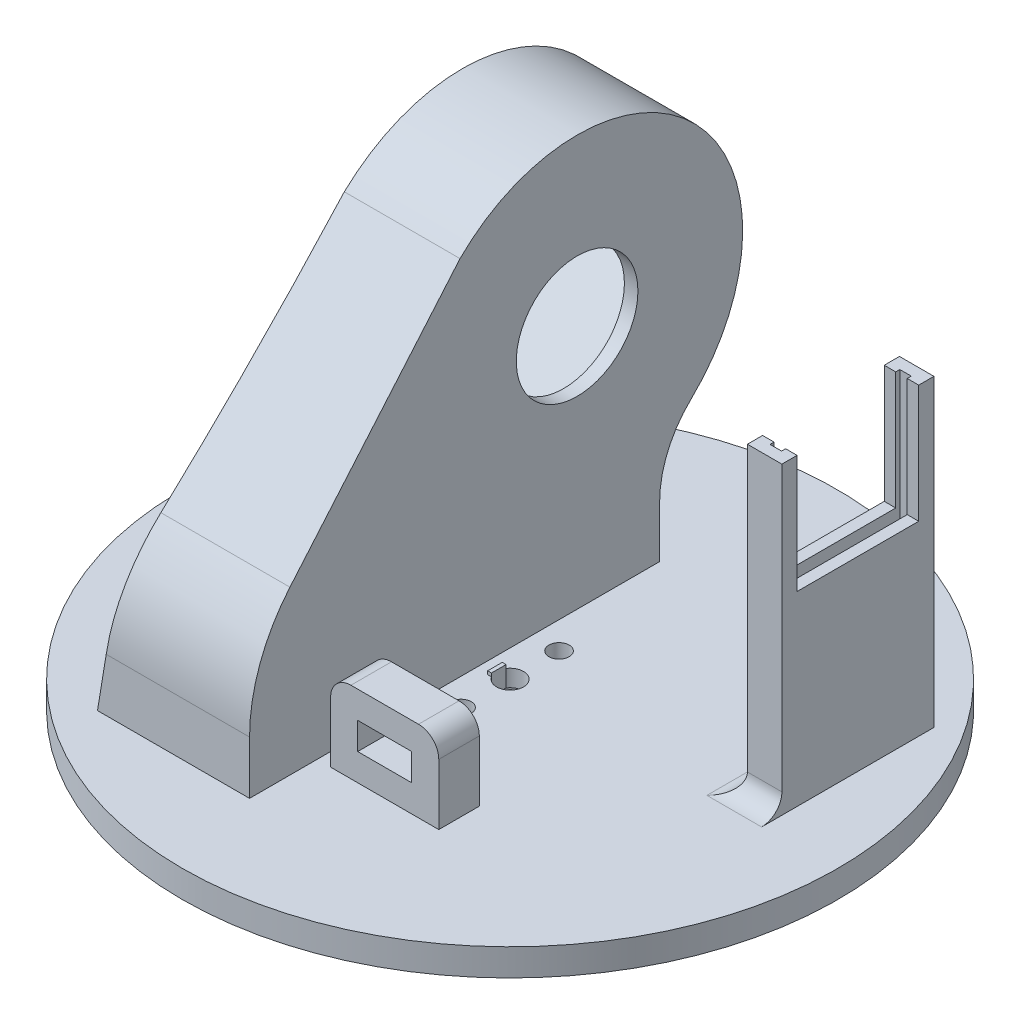
SolidWorks part; units mm, degrees
ref_plane "Front Plane" through (0, 0, 0) normal (0, 0, 1) x (1, 0, 0)
ref_plane "Top Plane" through (0, 0, 0) normal (0, 1, 0) x (1, 0, 0)
ref_plane "Right Plane" through (0, 0, 0) normal (1, 0, 0) x (0, 0, -1)
sketch "Sketch2" plane through (0, 0, 0) normal (0, 1, 0) x (1, 0, 0)
  circle A0 centre (0, 0) radius 48.5
  dimension "D1" = 97
extrude "Boss-Extrude1" add sketch "Sketch2" along normal blind 4
sketch "Sketch4" plane through (0, 0, 0) normal (0, -1, 0) x (1, 0, 0)
  circle A0 centre (0, 7.25) radius 1.5
  circle A1 centre (0, -7.25) radius 1.5
  dimension "D1" = 3
  dimension "D2" = 3
  dimension "D3" = 14.5
  dimension "D4" = 7.25
extrude "Cut-Extrude2" cut sketch "Sketch4" against normal through all
sketch "Sketch5" plane through (0, 0, 0) normal (0, -1, 0) x (1, 0, 0)
  circle A0 centre (0, 0) radius 3.75
  dimension "D1" = 7.5
extrude "Cut-Extrude3" cut sketch "Sketch5" against normal blind 1.5
ref_plane "Plane1" through (-4, 0, 0) normal (1, 0, 0) x (0, 0, -1)
sketch "Sketch7" plane through (-4, 0, 0) normal (1, 0, 0) x (0, 0, -1)
  line L0 (23.1299, 11.6445) -> (23.1299, 4)
  line L5 (48.5, 4) -> (-48.5, 4) construction
  line L6 (-27.2273, 29.5362) -> (-1.2843, 55.4793)
  line L7 (-43.5609, 4) -> (23.1299, 4)
  line L11 (-34.5496, 4) -> (-34.5496, 11.8586)
  arc A4 (28.7298, 24.692) -> (-1.2843, 55.4793) centre (13.9185, 40.2765) ccw
  arc A5 (28.7298, 24.692) -> (23.1299, 11.6445) centre (41.1299, 11.6445) ccw
  arc A6 (-27.2273, 29.5362) -> (-34.5496, 11.8586) centre (-9.5496, 11.8586) ccw
  dimension "D1" = 25
  dimension "D4" = 43
  dimension "D3" = 18
  dimension "D5" = 45
extrude "Boss-Extrude2" add sketch "Sketch7" against normal blind 14
ref_plane "Plane2" through (-6, 0, 0) normal (1, 0, 0) x (0, 0, -1)
sketch "Sketch8" plane through (-6, 0, 0) normal (1, 0, 0) x (0, 0, -1)
  line L0 (-27.2273, 29.5362) -> (-1.2843, 55.4793) construction
  line L1 (-15.2496, 25.9576) -> (13.7417, 54.9489)
  line L2 (-15.2496, 25.9576) -> (-0.4004, 11.1083)
  line L3 (-0.4004, 11.1083) -> (28.591, 40.0997)
  line L4 (13.7417, 54.9489) -> (28.591, 40.0997)
  line L5 (-15.2496, 25.9576) -> (28.591, 40.0997) construction
  line L6 (-0.4004, 11.1083) -> (13.7417, 54.9489) construction
  point P0 (6.6707, 33.0286)
  point P11 (13.9185, 40.2765)
  dimension "D1" = 41
  dimension "D2" = 21
  dimension "D3" = 90
  dimension "D4" = 20.5
  dimension "D5" = 90
  dimension "D6" = 10.25
  dimension "D7" = 10.5
extrude "Cut-Extrude5" cut sketch "Sketch8" against normal up to next
sketch "Sketch9" plane through (-18, 0, 0) normal (-1, 0, 0) x (0, 0, 1)
  line L0 (-13.7417, 54.9489) -> (-28.591, 40.0997) construction
  line L3 (-21.1664, 47.5243) -> (-22.536, 48.894) construction
  circle A0 centre (-20.1057, 53.5347) radius 1.3
  circle A1 centre (-27.1768, 46.4637) radius 1.3
  circle A2 centre (6.7644, 12.5225) radius 1.3
  circle A3 centre (13.8354, 19.5936) radius 1.3
  dimension "D1" = 2.6
  dimension "D5" = 5
  dimension "D6" = 90
  dimension "D2" = 3.5
  dimension "D3" = 2
  dimension "D4" = 2
extrude "Cut-Extrude6" cut sketch "Sketch9" against normal blind 7.5
sketch "Sketch11" plane through (-4, 0, 0) normal (1, 0, 0) x (0, 0, -1)
  circle A0 centre (13.9185, 40.2765) radius 9
  dimension "D1" = 18
extrude "Cut-Extrude9" cut sketch "Sketch11" against normal up to next
sketch "Sketch17" plane through (-18, 0, 0) normal (-1, 0, 0) x (0, 0, 1)
  line L0 (29.3486, 31.6576) -> (3.4056, 57.6006)
  line L1 (-26.1299, 11.6445) -> (-26.1299, 1)
  line L2 (-26.1299, 1) -> (37.5496, 1)
  line L3 (37.5496, 1) -> (37.5496, 11.8586)
  line L4 (27.2273, 29.5362) -> (1.2843, 55.4793)
  line L5 (-23.1299, 11.6445) -> (-23.1299, 4)
  line L6 (-23.1299, 4) -> (34.5496, 4)
  line L7 (34.5496, 4) -> (34.5496, 11.8586)
  line L9 (-23.1299, 11.6445) -> (-23.1299, 4)
  line L10 (-23.1299, 4) -> (34.5496, 4)
  line L11 (34.5496, 4) -> (34.5496, 11.8586)
  line L12 (-26.1299, 4) -> (37.5496, 4)
  line L13 (48.5, 4) -> (-48.5, 4) construction
  line L14 (3.4056, 57.6006) -> (28.5745, 28.0776)
  line L15 (1.2843, 55.4793) -> (26.295, 26.1272)
  line L16 (31.5496, 11.8586) -> (31.5496, 4)
  line L18 (27.2273, 29.5362) -> (1.2843, 55.4793) construction
  arc A0 (3.4056, 57.6006) -> (-30.7965, 22.5174) centre (-13.9185, 40.2765) ccw
  arc A1 (-26.1299, 11.6445) -> (-30.7965, 22.5174) centre (-41.1299, 11.6445) ccw
  arc A2 (37.5496, 11.8586) -> (29.3486, 31.6576) centre (9.5496, 11.8586) ccw
  arc A3 (1.2843, 55.4793) -> (-28.7298, 24.692) centre (-13.9185, 40.2765) ccw
  arc A4 (-23.1299, 11.6445) -> (-28.7298, 24.692) centre (-41.1299, 11.6445) ccw
  arc A5 (34.5496, 11.8586) -> (27.2273, 29.5362) centre (9.5496, 11.8586) ccw
  arc A6 (1.2843, 55.4793) -> (-28.7298, 24.692) centre (-13.9185, 40.2765) ccw
  arc A7 (-23.1299, 11.6445) -> (-28.7298, 24.692) centre (-41.1299, 11.6445) ccw
  arc A8 (34.5496, 11.8586) -> (27.2273, 29.5362) centre (9.5496, 11.8586) ccw
  arc A9 (31.5496, 11.8586) -> (25.106, 27.4149) centre (9.5496, 11.8586) ccw
  line M16 (27.2273, 29.5362) -> (1.2843, 55.4793)
  arc M17 (1.2843, 55.4793) -> (-28.7298, 24.692) centre (-13.9185, 40.2765) ccw
  arc M18 (-28.7298, 24.692) -> (-23.1299, 11.6445) centre (-41.1299, 11.6445) cw
  line M19 (-23.1299, 11.6445) -> (-23.1299, 4)
  line M21 (34.5496, 4) -> (34.5496, 11.8586)
  arc M22 (34.5496, 11.8586) -> (27.2273, 29.5362) centre (9.5496, 11.8586) ccw
  dimension "D1" = 0
  dimension "D2" = 3
  dimension "D3" = 3
extrude "Boss-Extrude7" add sketch "Sketch17" along normal blind 9 and the other way up to surface contours A9 L16 L12 L15 M21 M22 M16 | A1 L1 L12 L14 A0 M19 M18 M17 M16 M22 other way up to face at (-4, 40.2765, -22.9185)
sketch "Sketch25" plane through (-18, 0, 0) normal (-1, 0, 0) x (0, 0, 1)
  line L0 (-23.1299, 11.6445) -> (-23.1299, 4)
  line L1 (48.5, 4) -> (-48.5, 4) construction
  line L2 (-23.1299, 11.6445) -> (-23.1299, 4) construction
  line L3 (1.2843, 55.4793) -> (26.295, 26.1272) construction
  line L4 (31.5496, 4) -> (-23.1299, 4) construction
  line L5 (31.5496, 11.8586) -> (31.5496, 4) construction
  line L6 (31.5496, 4) -> (-23.1299, 4)
  line L7 (31.5496, 11.8586) -> (31.5496, 4)
  line L8 (1.2843, 55.4793) -> (26.295, 26.1272)
  arc A0 (-23.1299, 11.6445) -> (-28.7298, 24.692) centre (-41.1299, 11.6445) ccw construction
  arc A1 (1.2843, 55.4793) -> (-28.7298, 24.692) centre (-13.9185, 40.2765) ccw construction
  arc A2 (-23.1299, 11.6445) -> (-28.7298, 24.692) centre (-41.1299, 11.6445) ccw
  arc A3 (31.5496, 11.8586) -> (26.295, 26.1272) centre (9.5496, 11.8586) ccw construction
  arc A4 (31.5496, 11.8586) -> (26.295, 26.1272) centre (9.5496, 11.8586) ccw
  spline S0 degree 3 poles (-28.7298, 24.692) (-21.9549, 18.2532) (-19.0941, 12.798) (-15.1299, 4) knots 0 0 0 0 1 1 1 1
  spline S1 degree 2 poles (11.7516, 43.195) (26.5513, 25.8264) (25.5496, 4) knots 0 0 0 1 1 1
  dimension "D2" = 8
  dimension "D1" = 6
extrude "Boss-Extrude10" add sketch "Sketch25" along normal up to surface (9 mm away) contours S0 L6 L0 A2 | A4 S1 A2 S0 L8 up to face at (-27, 22.2911, 0.3951)
sketch "Sketch26" plane through (0, 0, 0) normal (0, 0, 1) x (1, 0, 0)
  line L0 (-4, 64.7765) -> (-27, 64.7765) construction
  line L1 (-27, 4) -> (-4, 4) construction
  line L2 (-27, 4) -> (-27, 11.8586) construction
  line L3 (-26, 64.7765) -> (-27, 64.7765)
  line L4 (-27, 64.7765) -> (-27, 4)
  line L5 (-27, 4) -> (-23, 4)
  spline S0 degree 2 poles (-26, 64.7765) (-24.7724, 34.3751) (-23, 4) knots 0 0 0 1 1 1
  dimension "D1" = 1
  dimension "D2" = 4
  dimension "D3" = 2
extrude "Cut-Extrude15" [suppressed] cut sketch "Sketch26" against normal through all both and the other way through all contours L4 L5 S0 L3
sketch "Sketch27" plane through (0, 4, 0) normal (0, 1, 0) x (1, 0, 0)
  line L1 (-2, -18.5496) -> (14, -18.5496)
  line L2 (-2, -18.5496) -> (-2, -24.5496)
  line L3 (-2, -24.5496) -> (14, -24.5496)
  line L4 (14, -18.5496) -> (14, -24.5496)
  line L5 (-27, -34.5496) -> (-4, -34.5496) construction
  line L6 (-4, -34.5496) -> (-4, 26.1299) construction
  dimension "D1" = 10
  dimension "D2" = 6
  dimension "D3" = 16
  dimension "D4" = 2
extrude "Boss-Extrude11" add sketch "Sketch27" along normal blind 12
fillet "Fillet6" radius 3 2 edges at (14, 16, 21.5496) (-2, 16, 21.5496)
sketch "Sketch28" plane through (0, 0, 24.5496) normal (0, 0, 1) x (1, 0, 0)
  line L8 (10, 12) -> (2, 12)
  line L9 (2, 12) -> (2, 8)
  line L10 (2, 8) -> (10, 8)
  line L11 (10, 8) -> (10, 12)
  line L12 (10, 12) -> (2, 12)
  line L13 (2, 12) -> (2, 8)
  line L14 (2, 8) -> (10, 8)
  line L15 (10, 8) -> (10, 12)
  dimension "D1" = 4
extrude "Cut-Extrude16" cut sketch "Sketch28" against normal up to next
sketch "Sketch29" plane through (0, 0, 0) normal (0, 0, 1) x (1, 0, 0)
  line L0 (-4, 64.7765) -> (-27, 64.7765) construction
  line L1 (-27, 4) -> (-4, 4) construction
  line L2 (-21, 64.7765) -> (-27, 64.7765)
  line L3 (-27, 64.7765) -> (-27, 4)
  line L4 (-27, 4) -> (-26.5, 4)
  line L5 (48.5, 4) -> (-48.5, 4) construction
  spline S0 degree 2 poles (-21, 64.7765) (-21.2205, 34.1409) (-26.5, 4) knots 0 0 0 1 1 1
  dimension "D1" = 6
  dimension "D2" = 4
  dimension "D3" = 0.5
  dimension "D4" = 25
extrude "Cut-Extrude17" cut sketch "Sketch29" against normal through all both and the other way through all
sketch "Croquis4" plane through (0, 4, 0) normal (0, 1, 0) x (1, 0, 0)
  line L1 (32.45, 2.6699) -> (37.55, 2.6699)
  line L2 (32.45, 2.6699) -> (32.45, 25.1699)
  line L3 (32.45, 25.1699) -> (37.55, 25.1699)
  line L4 (37.55, 2.6699) -> (37.55, 25.1699)
  line L5 (32.45, 2.6699) -> (37.55, 25.1699) construction
  line L6 (32.45, 25.1699) -> (37.55, 2.6699) construction
  line L8 (-4, 26.1299) -> (-26.5, 26.1299) construction
  line L9 (-4, -34.5496) -> (-4, 26.1299) construction
  point P0 (35, 13.9199)
  dimension "D1" = 12.21
  dimension "D2" = 39
  dimension "D3" = 5.1
  dimension "D4" = 22.5
extrude "Saliente-Extruir1" add sketch "Croquis4" along normal blind 45
sketch "Croquis5" plane through (0, 49, 0) normal (0, 1, 0) x (1, 0, 0)
  line L0 (37.55, 2.6699) -> (37.55, 25.1699) construction
  line L1 (34.15, 4.3199) -> (35.85, 4.3199)
  line L2 (34.15, 4.3199) -> (34.15, 23.5199)
  line L3 (34.15, 23.5199) -> (35.85, 23.5199)
  line L4 (35.85, 4.3199) -> (35.85, 23.5199)
  line L5 (34.15, 4.3199) -> (35.85, 23.5199) construction
  line L6 (34.15, 23.5199) -> (35.85, 4.3199) construction
  line L7 (37.55, 25.1699) -> (32.45, 25.1699) construction
  point P0 (35, 13.9199)
  dimension "D1" = 1.7
  dimension "D2" = 2.55
  dimension "D3" = 11.25
  dimension "D4" = 19.2
extrude "Cortar-Extruir1" cut sketch "Croquis5" against normal blind 19.5
sketch "Croquis6" plane through (37.55, 0, 0) normal (1, 0, 0) x (0, 0, -1)
  line L0 (2.6699, 49) -> (25.1699, 49) construction
  line L1 (4.9185, 31.553) -> (22.9185, 31.553)
  line L2 (4.9185, 31.553) -> (4.9185, 49)
  line L3 (4.9185, 49) -> (22.9185, 49)
  line L4 (22.9185, 31.553) -> (22.9185, 49)
  line L5 (4.9185, 31.553) -> (22.9185, 49) construction
  line L6 (4.9185, 49) -> (22.9185, 31.553) construction
  point P0 (13.9185, 40.2765)
extrude "Cortar-Extruir2" cut sketch "Croquis6" against normal blind 19.5
fillet "Redondeo1" radius 3 2 edges at (35, 4, -2.6699) (32.45, 4, -13.9199)
sketch "Croquis7" plane through (0, 1.5, 0) normal (0, -1, 0) x (1, 0, 0)
  line L0 (-1.67, -1.0822) -> (-1.67, 1.0822)
  line L1 (-1.67, -1.0822) -> (-1.67, 1.0822)
  circle A0 centre (0, 0) radius 1.99
  dimension "D1" = 3.98
  dimension "D2" = 1.67
extrude "Cortar-Extruir3" cut sketch "Croquis7" against normal blind 10 contours A0
sketch "Croquis8" plane through (0, 1.5, 0) normal (0, -1, 0) x (1, 0, 0)
  line L0 (-1.67, 1.0822) -> (-1.67, -1.0822)
  line L1 (-1.67, 1.0822) -> (-2.2341, 1.0822)
  line L2 (-2.2341, 1.0822) -> (-2.2341, -1.0822)
  line L3 (-2.2341, -1.0822) -> (-1.67, -1.0822)
  circle A0 centre (0, 0) radius 1.99 construction
  dimension "D1" = 1.67
extrude "Saliente-Extruir2" add sketch "Croquis8" against normal blind 3
